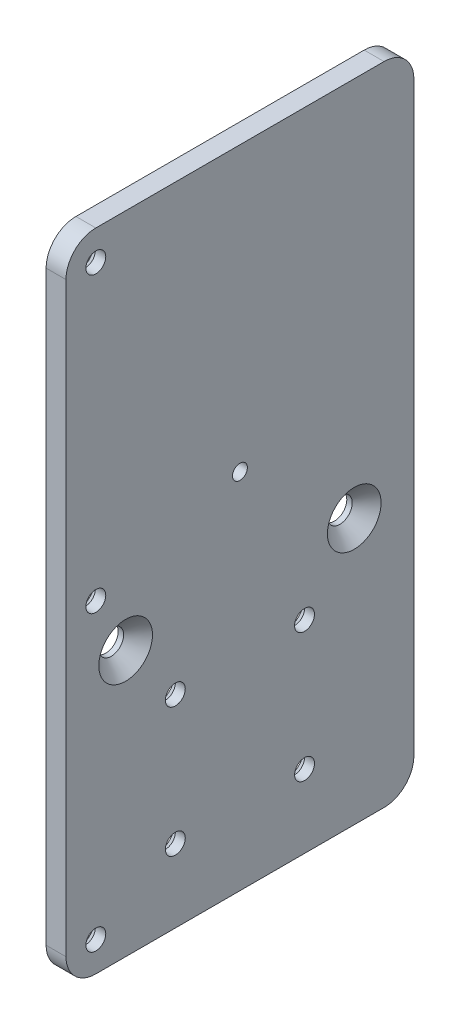
SolidWorks part; units mm, degrees
ref_plane "Спереди" through (0, 0, 0) normal (0, 0, 1) x (1, 0, 0)
ref_plane "Сверху" through (0, 0, 0) normal (0, 1, 0) x (1, 0, 0)
ref_plane "Справа" through (0, 0, 0) normal (1, 0, 0) x (0, 0, -1)
sketch "Эскиз1" plane through (0, 0, 0) normal (1, 0, 0) x (0, 0, -1)
  line L1 (-19.9981, 61.0682) -> (50.0019, 61.0682)
  line L2 (-19.9981, 61.0682) -> (-19.9981, -68.9318)
  line L3 (-19.9981, -68.9318) -> (50.0019, -68.9318)
  line L4 (50.0019, 61.0682) -> (50.0019, -68.9318)
  dimension "D1" = 70
  dimension "D2" = 130
extrude "Бобышка-Вытянуть1" add sketch "Эскиз1" along normal blind 4
sketch "Эскиз2" plane through (0, 0, 0) normal (-1, 0, 0) x (0, 0, 1)
  circle A0 centre (-28.0017, -28.2317) radius 2
  circle A1 centre (-28.0017, -54.2317) radius 2
  circle A2 centre (-2.0017, -28.2317) radius 2
  circle A3 centre (-2.0017, -54.2317) radius 2
  dimension "D1" = 4
  dimension "D2" = 4
  dimension "D3" = 4
  dimension "D4" = 4
extrude "Вырез-Вытянуть1" cut sketch "Эскиз2" against normal blind 10
fillet "Скругление1" radius 6 4 edges at (2, -68.9318, -50.0019) (2, -68.9318, 19.9981) (2, 61.0682, -50.0019) (2, 61.0682, 19.9981)
chamfer "Фаска1" distance 2 angle 45 4 edges at (0, -54.2317, -0.0017) (0, -28.2317, -0.0017) (0, -54.2317, -26.0017) (0, -28.2317, -26.0017)
sketch "Эскиз3" plane through (0, 0, 0) normal (-1, 0, 0) x (0, 0, 1)
  line L0 (19.9981, -3.9318) -> (-50.0019, -3.9318) construction
  line L1 (19.9981, 55.0682) -> (19.9981, -62.9318) construction
  line L2 (-50.0019, -62.9318) -> (-50.0019, 55.0682) construction
  line L3 (13.9981, 55.0682) -> (13.9981, -62.9318) construction
  circle A0 centre (13.9981, 55.0682) radius 2
  circle A1 centre (13.9981, -62.9318) radius 2
  circle A2 centre (13.9981, -3.9318) radius 2
  dimension "D1" = 4
  dimension "D2" = 4
  dimension "D3" = 4
extrude "Вырез-Вытянуть2" cut sketch "Эскиз3" against normal blind 15
chamfer "Фаска2" distance 1.9 angle 45 3 edges at (0, 55.0682, 15.9981) (0, -3.9318, 15.9981) (0, -62.9318, 15.9981)
sketch "Эскиз4" plane through (4, 0, 0) normal (1, 0, 0) x (0, 0, -1)
  circle A0 centre (-7.9981, -15.5318) radius 2.5
  circle A1 centre (38.0019, -15.5318) radius 2.5
  dimension "D1" = 5
  dimension "D2" = 5
extrude "Вырез-Вытянуть3" cut sketch "Эскиз4" against normal blind 15
chamfer "Фаска3" distance 2.9 angle 45 2 edges at (4, -15.5318, -40.5019) (4, -15.5318, 5.4981)
sketch "Эскиз5" plane through (0, 0, 0) normal (-1, 0, 0) x (0, 0, 1)
  line L0 (-15.0019, 61.0682) -> (-15.0019, -68.9318) construction
  line L1 (-44.0019, 61.0682) -> (13.9981, 61.0682) construction
  line L2 (13.9981, -68.9318) -> (-44.0019, -68.9318) construction
  circle A0 centre (-15.0019, 4.0682) radius 1.5
  dimension "D1" = 3
  dimension "D2" = 57
extrude "Вырез-Вытянуть4" cut sketch "Эскиз5" against normal blind 12
